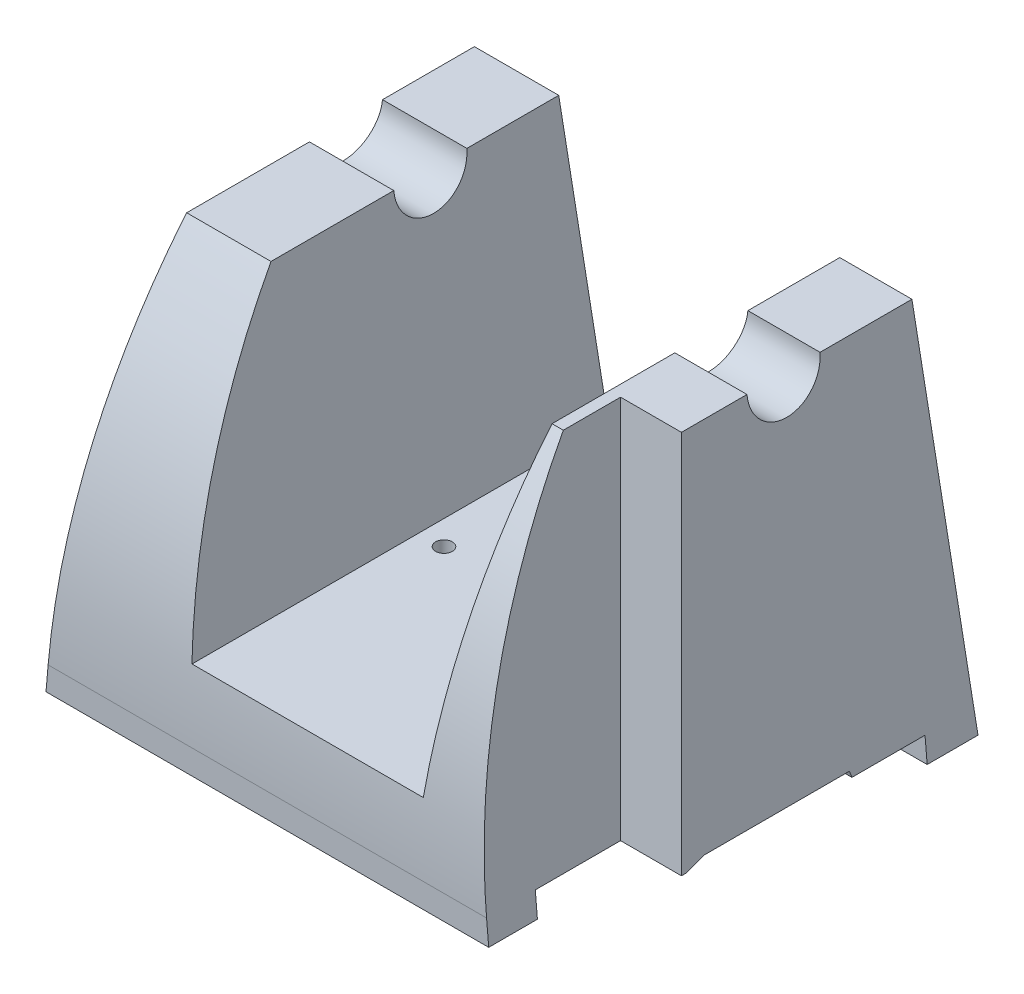
SolidWorks part; units mm, degrees
material "6061 Alloy"
ref_plane "Front Plane" through (0, 0, 0) normal (0, 0, 1) x (1, 0, 0)
ref_plane "Top Plane" through (0, 0, 0) normal (0, 1, 0) x (1, 0, 0)
ref_plane "Right Plane" through (0, 0, 0) normal (1, 0, 0) x (0, 0, -1)
sketch "Sketch1" plane through (0, 0, 0) normal (1, 0, 0) x (0, 0, -1)
  line L0 (0, 0) -> (0, 6.35)
  line L1 (28.0591, 98.425) -> (60.0671, 98.425)
  line L2 (111.125, 98.425) -> (111.125, 0)
  line L3 (111.125, 0) -> (98.425, 0)
  line L4 (98.425, 0) -> (98.425, 6.35)
  line L5 (98.425, 6.35) -> (79.375, 6.35)
  line L6 (79.375, 6.35) -> (78.8395, 7.9375)
  line L7 (78.8395, 7.9375) -> (40.8808, 7.9375)
  line L8 (40.8808, 7.9375) -> (36.1749, 6.35)
  line L9 (36.1749, 6.35) -> (12.7, 6.35)
  line L10 (12.7, 6.35) -> (12.7, 0)
  line L11 (12.7, 0) -> (0, 0)
  line L12 (28.0591, 98.425) -> (28.0591, 70.551) construction
  line L13 (79.1171, 98.425) -> (111.125, 98.425)
  line L14 (28.0591, 98.425) -> (111.125, 98.425) construction
  arc A0 (0, 6.35) -> (28.0591, 98.425) centre (165.1, 6.35) cw
  arc A1 (60.0671, 98.425) -> (79.1171, 98.425) centre (69.5921, 98.425) ccw
  dimension "D8" = 165.1
  dimension "D10" = 19.05
  dimension "D1" = 6.35
  dimension "D2" = 1.5875
  dimension "D3" = 12.7
  dimension "D4" = 12.7
  dimension "D5" = 6.35
  dimension "D6" = 19.05
  dimension "D7" = 98.425
  dimension "D9" = 111.125
extrude "Boss-Extrude1" add sketch "Sketch1" along normal blind 130.175
sketch "Sketch2" plane through (0, 0, -111.125) normal (0, 0, -1) x (-1, 0, 0)
  line L0 (-95.25, 98.425) -> (-95.25, 24.3211)
  line L1 (-130.175, 98.425) -> (0, 98.425) construction
  line L2 (-95.25, 24.3211) -> (-38.1, 24.3211)
  line L3 (-38.1, 24.3211) -> (-38.1, 98.425)
  line L4 (-130.175, 0) -> (-130.175, 98.425) construction
  line L5 (0, 0) -> (0, 98.425) construction
  line M4 (0, 98.425) -> (-130.175, 98.425)
  dimension "D1" = 34.925
  dimension "D2" = 38.1
extrude "Cut-Extrude1" cut sketch "Sketch2" against normal through all and the other way through all contours L2 L3 L0 M4
sketch "Sketch3" plane through (0, 98.425, 0) normal (0, 1, 0) x (1, 0, 0)
  line L0 (130.175, 111.125) -> (95.25, 111.125) construction
  line L1 (130.175, 0) -> (114.3, 0)
  line L2 (130.175, 0) -> (130.175, 34.925)
  line L3 (130.175, 34.925) -> (114.3, 34.925)
  line L4 (114.3, 0) -> (114.3, 34.925)
  dimension "D1" = 15.875
  dimension "D2" = 76.2
extrude "Cut-Extrude2" cut sketch "Sketch3" against normal through all
draft "Draft1" type of draft neutral plane draft angle 5 faces to draft 7 face at (65.8812, 55.2928, -111.125) face at (122.2375, 52.3875, -34.925) face at (130.175, 35.4542, -71.9504) face at (114.3, 31.1415, -16.6357) face at (95.25, 72.4097, -64.3304) face at (0, 28.926, -56.0103) face at (38.1, 72.4097, -64.3304) neutral plane through (130.175, 6.35, -36.1749) neutral plane normal (0, -1, 0) reverse direction yes parameters "D1"=5
sketch "Sketch4" plane through (0, 24.3211, 0) normal (0, 1, 0) x (1, 0, 0)
  circle A0 centre (42.8697, 60.325) radius 2.1784
  point P3 (42.8697, 50.8)
  point P4 (42.8697, 60.325)
extrude "Cut-Extrude3" cut sketch "Sketch4" against normal through all both and the other way through all
